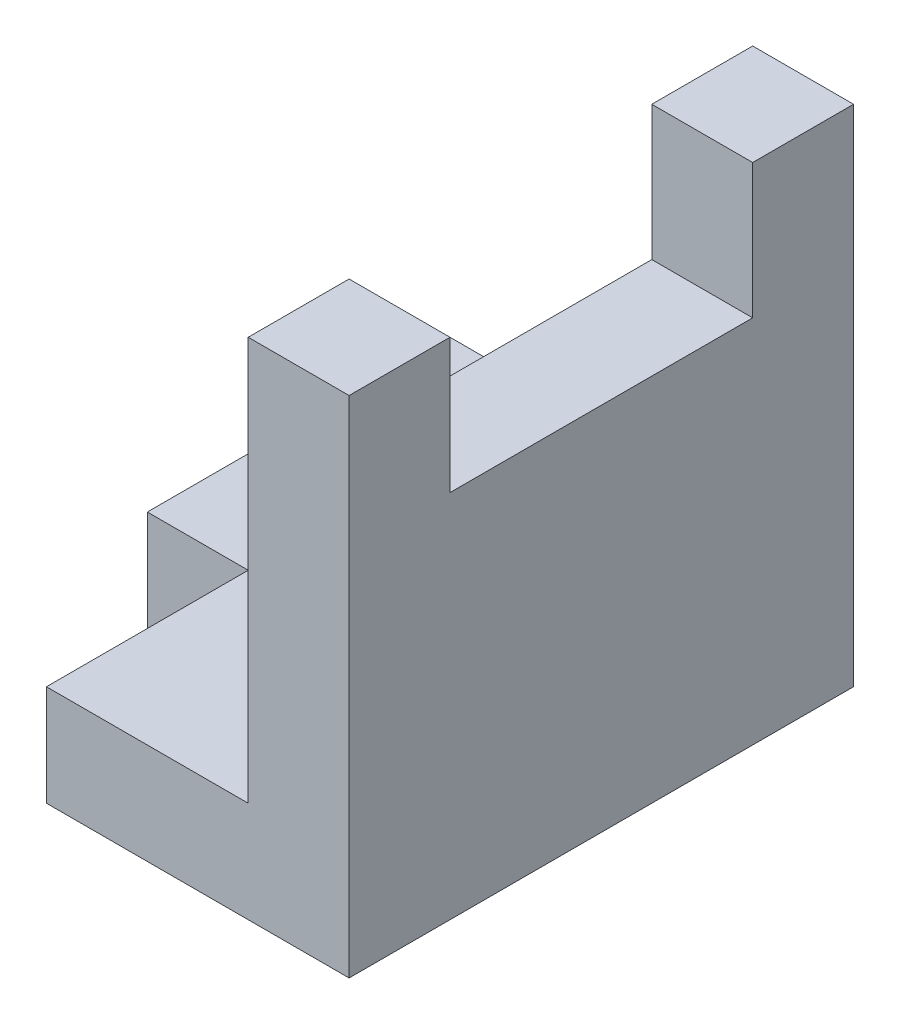
SolidWorks part; units mm, degrees
ref_plane "Front Plane" through (0, 0, 0) normal (0, 0, 1) x (1, 0, 0)
ref_plane "Top Plane" through (0, 0, 0) normal (0, 1, 0) x (1, 0, 0)
ref_plane "Right Plane" through (0, 0, 0) normal (1, 0, 0) x (0, 0, -1)
sketch "Sketch6" plane through (0, 0, 0) normal (0, 0, 1) x (1, 0, 0)
  line L1 (0, 0) -> (-1524, 0)
  line L2 (0, 0) -> (0, 381)
  line L3 (0, 381) -> (-1524, 381)
  line L4 (-1524, 0) -> (-1524, 381)
  line L5 (0, 0) -> (-381, 0)
  line L6 (0, 0) -> (0, 1905)
  line L7 (0, 1905) -> (-381, 1905)
  line L8 (-381, 0) -> (-381, 1905)
  dimension "D1" = 1524
  dimension "D2" = 381
  dimension "D3" = 1905
  dimension "D4" = 381
extrude "Boss-Extrude3" add sketch "Sketch6" along normal blind 1905 contours L8 L1 L2 L3 | L1 L8 L3 L4 | L8 L3 L6 L7
sketch "Sketch7" plane through (0, 1905, 0) normal (0, 1, 0) x (1, 0, 0)
  line L0 (0, -1905) -> (0, 0) construction
  line L1 (0, -1524) -> (-381, -1524)
  line L2 (0, -1524) -> (0, -381)
  line L3 (0, -381) -> (-381, -381)
  line L4 (-381, -1524) -> (-381, -381)
  line L5 (-381, -1905) -> (-381, 0) construction
  line L6 (0, -1905) -> (-381, -1905) construction
  dimension "D1" = 1143
  dimension "D2" = 381
extrude "Cut-Extrude1" cut sketch "Sketch7" against normal blind 508
sketch "Sketch9" plane through (0, 0, 1905) normal (0, 0, 1) x (1, 0, 0)
  line L0 (0, 0) -> (-1524, 0) construction
  line L1 (-1524, 381) -> (-1143, 381)
  line L2 (-1524, 381) -> (-1524, 0)
  line L3 (-1524, 0) -> (-1143, 0)
  line L4 (-1143, 381) -> (-1143, 0)
  dimension "D1" = 381
extrude "Cut-Extrude3" cut sketch "Sketch9" against normal blind 762
